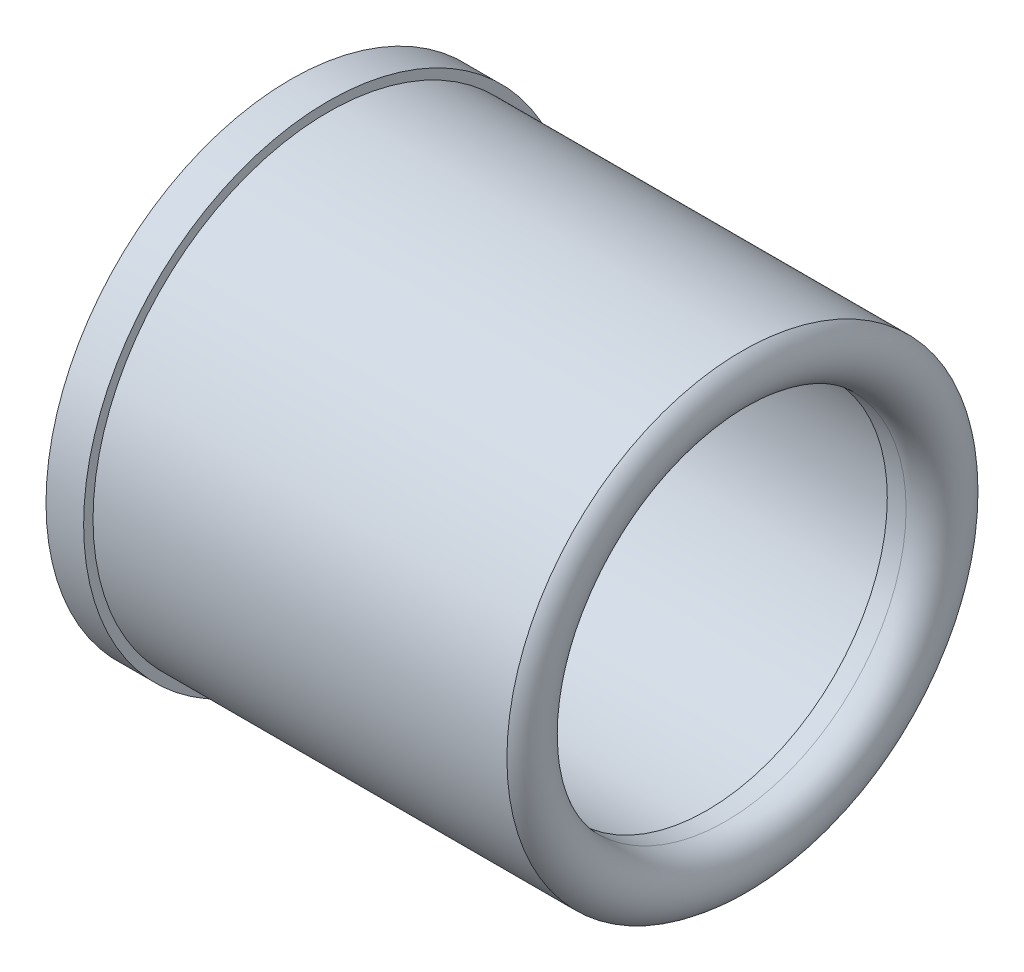
SolidWorks part; units mm, degrees
ref_plane "Front Plane" through (0, 0, 0) normal (0, 0, 1) x (1, 0, 0)
ref_plane "Top Plane" through (0, 0, 0) normal (0, 1, 0) x (1, 0, 0)
ref_plane "Right Plane" through (0, 0, 0) normal (1, 0, 0) x (0, 0, -1)
ref_plane "Plane1" through (0, 0, 0) normal (0, 0, -1) x (-1, 0, 0)
sketch "Sketch1" plane through (0, 0, 0) normal (0, 0, -1) x (-1, 0, 0)
  line L0 (-11.9728, -3.7333) -> (-11.9728, -3.4833)
  line L1 (-11.9728, -3.4833) -> (-0.9121, -3.4833)
  line L2 (-0.9121, -3.4833) -> (-0.9121, -2.0333)
  line L3 (-0.9121, -2.0333) -> (-1.9121, -2.0333)
  line L4 (-1.9121, -2.0333) -> (-1.9121, -2.2833)
  line L5 (-1.9121, -2.2833) -> (-12.9121, -2.2833)
  line L6 (-12.4728, -3.7333) -> (-11.9728, -3.7333)
  line L7 (-12.1757, -8.5333) -> (0.2029, -8.5333) construction
  arc A0 (-12.9121, -2.2833) -> (-12.4728, -3.7333) centre (-12.4728, -2.9417) ccw
  dimension "D1" = 11
  dimension "D2" = 5.05
  dimension "D3" = 0.25
  dimension "D4" = 0.25
  dimension "D5" = 6.5
  dimension "D6" = 1
  dimension "D7" = 0.5
revolve "Revolve1" add sketch "Sketch1" angle 360 about L7
